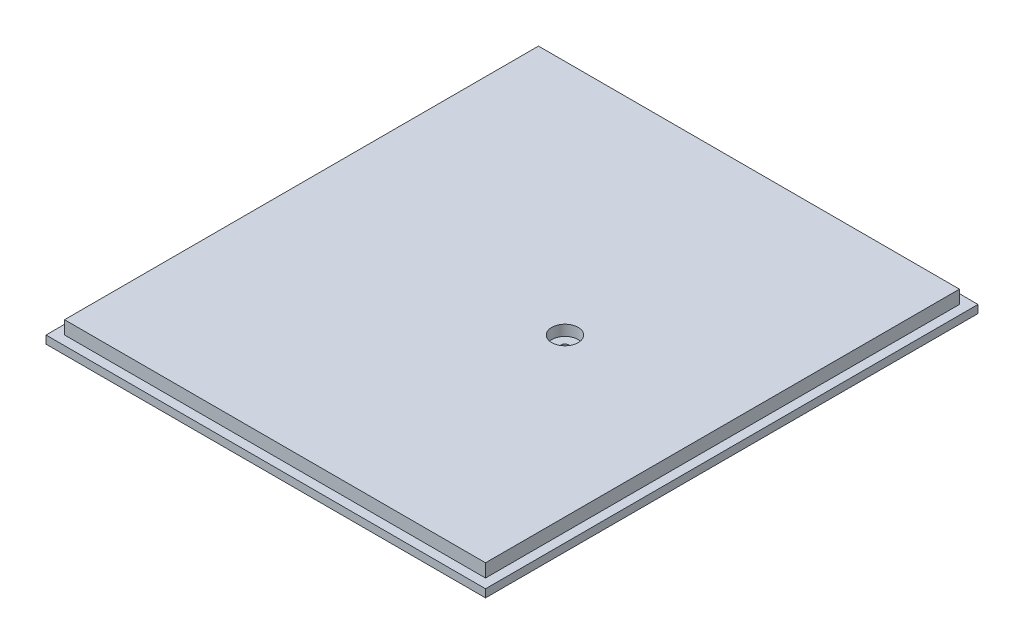
SolidWorks part; units mm, degrees
ref_plane "Front Plane" through (0, 0, 0) normal (0, 0, 1) x (1, 0, 0)
ref_plane "Top Plane" through (0, 0, 0) normal (0, 1, 0) x (1, 0, 0)
ref_plane "Right Plane" through (0, 0, 0) normal (1, 0, 0) x (0, 0, -1)
sketch "Sketch1" plane through (0, 0, 0) normal (0, 1, 0) x (1, 0, 0)
  line L1 (-65.8056, 49.5639) -> (100.1944, 49.5639)
  line L2 (-65.8056, 49.5639) -> (-65.8056, -136.4361)
  line L3 (-65.8056, -136.4361) -> (100.1944, -136.4361)
  line L4 (100.1944, 49.5639) -> (100.1944, -136.4361)
  dimension "D1" = 166
  dimension "D2" = 186
extrude "Boss-Extrude2" add sketch "Sketch1" along normal blind 3
sketch "Sketch2" plane through (0, 3, 0) normal (0, 1, 0) x (1, 0, 0)
  line L0 (100.1944, 49.5639) -> (-65.8056, 49.5639) construction
  line L1 (-62.3056, 46.0639) -> (96.6944, 46.0639)
  line L2 (-62.3056, 46.0639) -> (-62.3056, -132.9361)
  line L3 (-62.3056, -132.9361) -> (96.6944, -132.9361)
  line L4 (96.6944, 46.0639) -> (96.6944, -132.9361)
  line L5 (-65.8056, -136.4361) -> (100.1944, -136.4361) construction
  line L6 (-65.8056, 49.5639) -> (-65.8056, -136.4361) construction
  line L7 (100.1944, -136.4361) -> (100.1944, 49.5639) construction
  dimension "D1" = 3.5
  dimension "D2" = 3.5
  dimension "D3" = 3.5
  dimension "D4" = 3.5
extrude "Boss-Extrude3" add sketch "Sketch2" along normal blind 5
sketch "Sketch3" plane through (0, 0, 0) normal (0, -1, 0) x (-1, 0, 0)
  line L0 (-17.1944, 49.5639) -> (-17.1944, -136.4361) construction
  line L1 (-100.1944, 49.5639) -> (65.8056, 49.5639) construction
  line L2 (65.8056, -136.4361) -> (-100.1944, -136.4361) construction
  text T0 "MemoMat\r\n" font "Century Gothic" height in points 60
extrude "Cut-Extrude3" cut sketch "Sketch3" against normal blind 4
sketch "Sketch6" plane through (0, 0, 0) normal (0, -1, 0) x (1, 0, 0)
  line L0 (37.1944, -49.5639) -> (37.1944, 136.4361) construction
  line L1 (100.1944, -49.5639) -> (-65.8056, -49.5639) construction
  line L2 (-65.8056, 136.4361) -> (100.1944, 136.4361) construction
  circle A0 centre (37.1944, 43.4361) radius 1.5
  dimension "D2" = 3
  dimension "D1" = 20
extrude "Cut-Extrude6" cut sketch "Sketch6" against normal blind 8
sketch "Sketch7" plane through (0, 8, 0) normal (0, 1, 0) x (1, 0, 0)
  circle A0 centre (37.1944, -43.4361) radius 5
  dimension "D1" = 10
extrude "Cut-Extrude7" cut sketch "Sketch7" against normal blind 4
